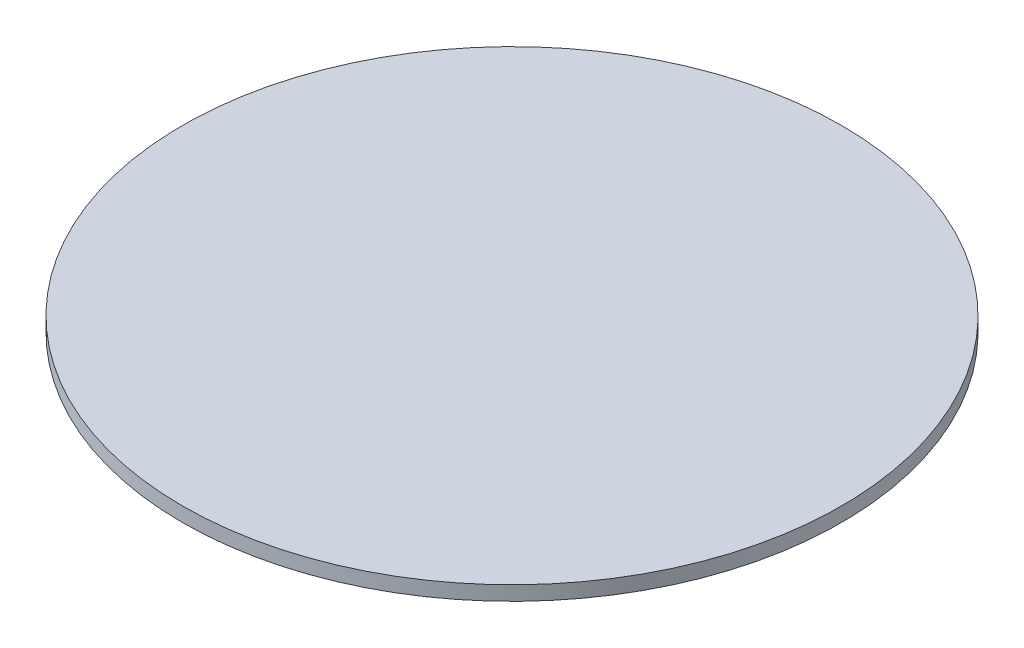
SolidWorks part; units mm, degrees
ref_plane "Front Plane" through (0, 0, 0) normal (0, 0, 1) x (1, 0, 0)
ref_plane "Top Plane" through (0, 0, 0) normal (0, 1, 0) x (1, 0, 0)
ref_plane "Right Plane" through (0, 0, 0) normal (1, 0, 0) x (0, 0, -1)
sketch "Sketch2" plane through (0, 0, 0) normal (0, 1, 0) x (1, 0, 0)
  circle A0 centre (0, 0) radius 58.2057
extrude "Boss-Extrude1" add sketch "Sketch2" along normal blind 2.54
